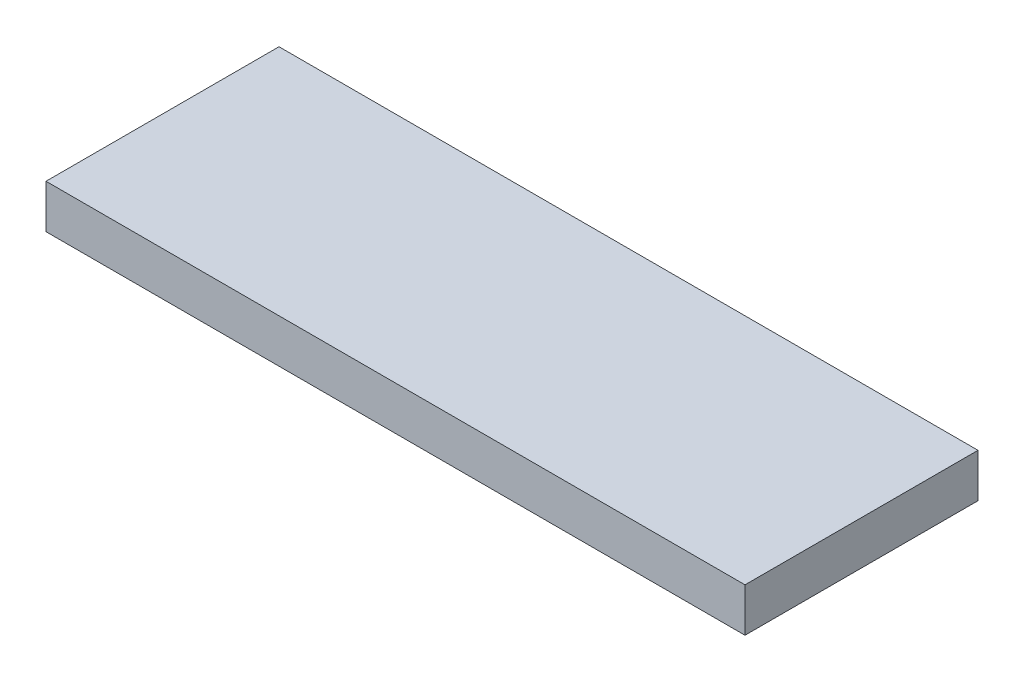
SolidWorks part; units mm, degrees
ref_plane "Front Plane" through (0, 0, 0) normal (0, 0, 1) x (1, 0, 0)
ref_plane "Top Plane" through (0, 0, 0) normal (0, 1, 0) x (1, 0, 0)
ref_plane "Right Plane" through (0, 0, 0) normal (1, 0, 0) x (0, 0, -1)
sketch "Sketch1" plane through (0, 0, 0) normal (0, 1, 0) x (1, 0, 0)
  line L0 (0, 0) -> (76.2, 0)
  line L1 (76.2, 0) -> (76.2, 25.4)
  line L2 (76.2, 25.4) -> (0, 25.4)
  line L3 (0, 25.4) -> (0, 0)
  dimension "D1" = 76.2
  dimension "D2" = 25.4
extrude "Boss-Extrude1" add sketch "Sketch1" along normal blind 4.7625
